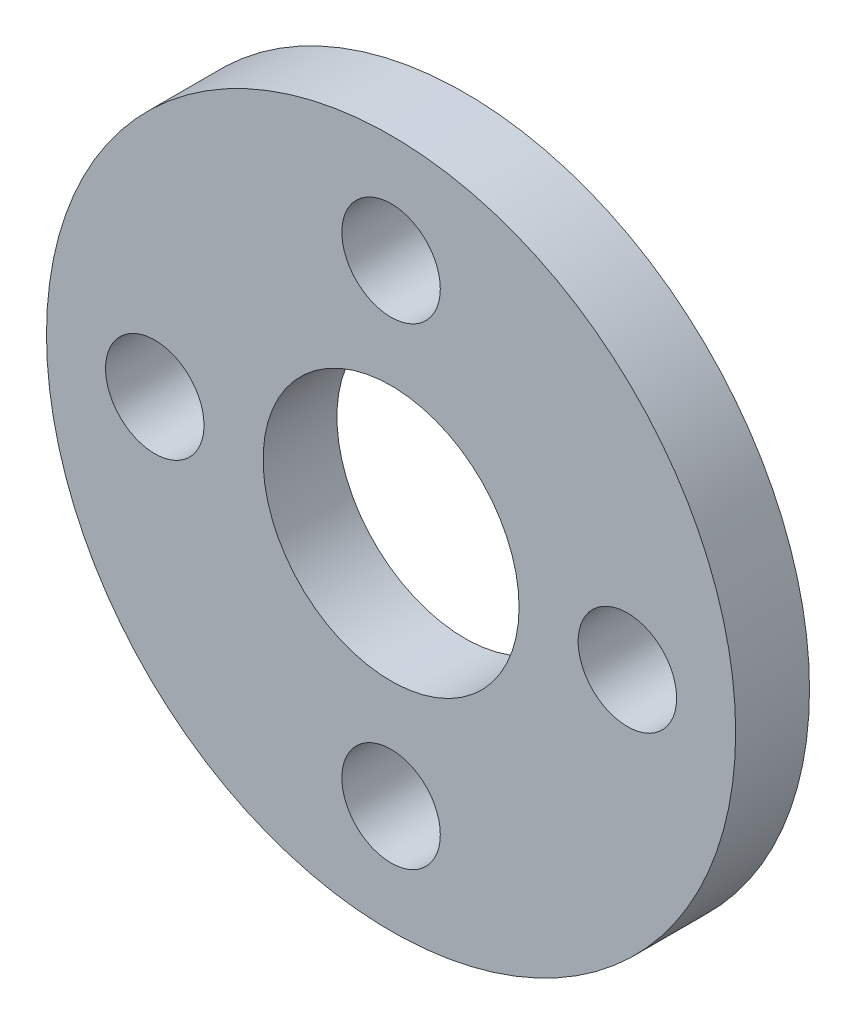
SolidWorks part; units mm, degrees
ref_plane "Спереди" through (0, 0, 0) normal (0, 0, 1) x (1, 0, 0)
ref_plane "Сверху" through (0, 0, 0) normal (0, 1, 0) x (1, 0, 0)
ref_plane "Справа" through (0, 0, 0) normal (1, 0, 0) x (0, 0, -1)
sketch "Эскиз1" plane through (0, 0, 0) normal (0, 0, 1) x (1, 0, 0)
  line L0 (0, 0) -> (-10.0954, 0) construction
  circle A0 centre (0, 0) radius 7
  circle A1 centre (0, 0) radius 2.6
  circle A2 centre (-4.8, 0) radius 1
  circle A3 centre (0, 4.8) radius 1
  circle A4 centre (4.8, 0) radius 1
  circle A5 centre (0, -4.8) radius 1
  point P16 (0, 0)
  dimension "D1" = 5.2
  dimension "D2" = 14
  dimension "D3" = 2
  dimension "D4" = 4.8
  dimension "D5" = 4
extrude "Бобышка-Вытянуть1" add sketch "Эскиз1" along normal blind 1.5
